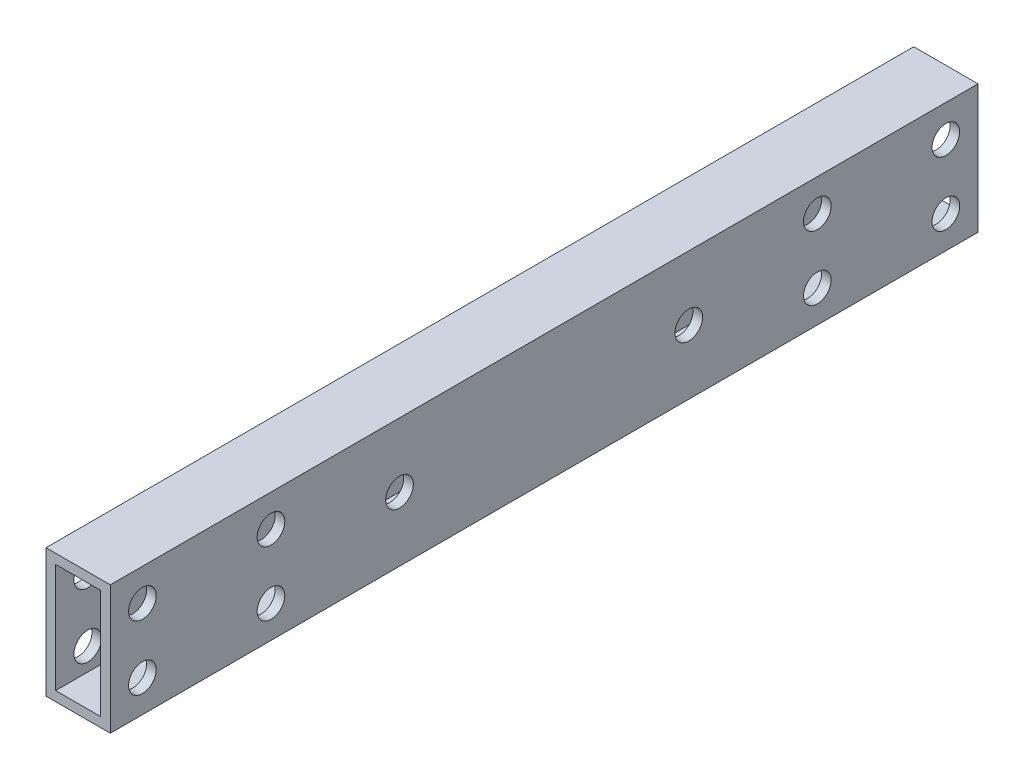
SolidWorks part; units mm, degrees
material "5052-H34"
ref_plane "正面" through (0, 0, 0) normal (0, 0, 1) x (1, 0, 0)
ref_plane "平面" through (0, 0, 0) normal (0, 1, 0) x (1, 0, 0)
ref_plane "右側面" through (0, 0, 0) normal (1, 0, 0) x (0, 0, -1)
sketch "ｽｹｯﾁ1" plane through (0, 0, 0) normal (0, 0, 1) x (1, 0, 0)
  line L1 (0, 0) -> (10, 0)
  line L2 (0, 0) -> (0, 20)
  line L3 (0, 20) -> (10, 20)
  line L4 (10, 0) -> (10, 20)
  dimension "D1" = 10
  dimension "D2" = 20
extrude "押し出し-薄板1" add sketch "ｽｹｯﾁ1" along normal blind 135 thin thin type one direction reverse wall 1.5
sketch "ｽｹｯﾁ3" plane through (10, 0, 0) normal (1, 0, 0) x (0, 0, -1)
  line L0 (-135, 20) -> (0, 20) construction
  line L1 (-135, 0) -> (-135, 20) construction
  line L2 (-135, 10) -> (0, 10) construction
  line L3 (0, 0) -> (0, 20) construction
  line L4 (-67.5, 20) -> (-67.5, 0) construction
  line L5 (-135, 0) -> (0, 0) construction
  circle A0 centre (-130, 15) radius 2.15
  circle A1 centre (-110, 15) radius 2.15
  circle A6 centre (-25, 15) radius 2.15
  circle A7 centre (-5, 15) radius 2.15
  circle A8 centre (-5, 5) radius 2.15
  circle A9 centre (-25, 5) radius 2.15
  circle A10 centre (-110, 5) radius 2.15
  circle A11 centre (-130, 5) radius 2.15
  circle A12 centre (-45, 10) radius 2.15
  circle A13 centre (-90, 10) radius 2.15
  dimension "D1" = 4.3
  dimension "D2" = 5
  dimension "D3" = 5
  dimension "D4" = 20
  dimension "D5" = 4.3
  dimension "D6" = 45
extrude "ｶｯﾄ - 押し出し2" cut sketch "ｽｹｯﾁ3" against normal up to surface (10 mm away) up to face at (0, 10, 67.5)
